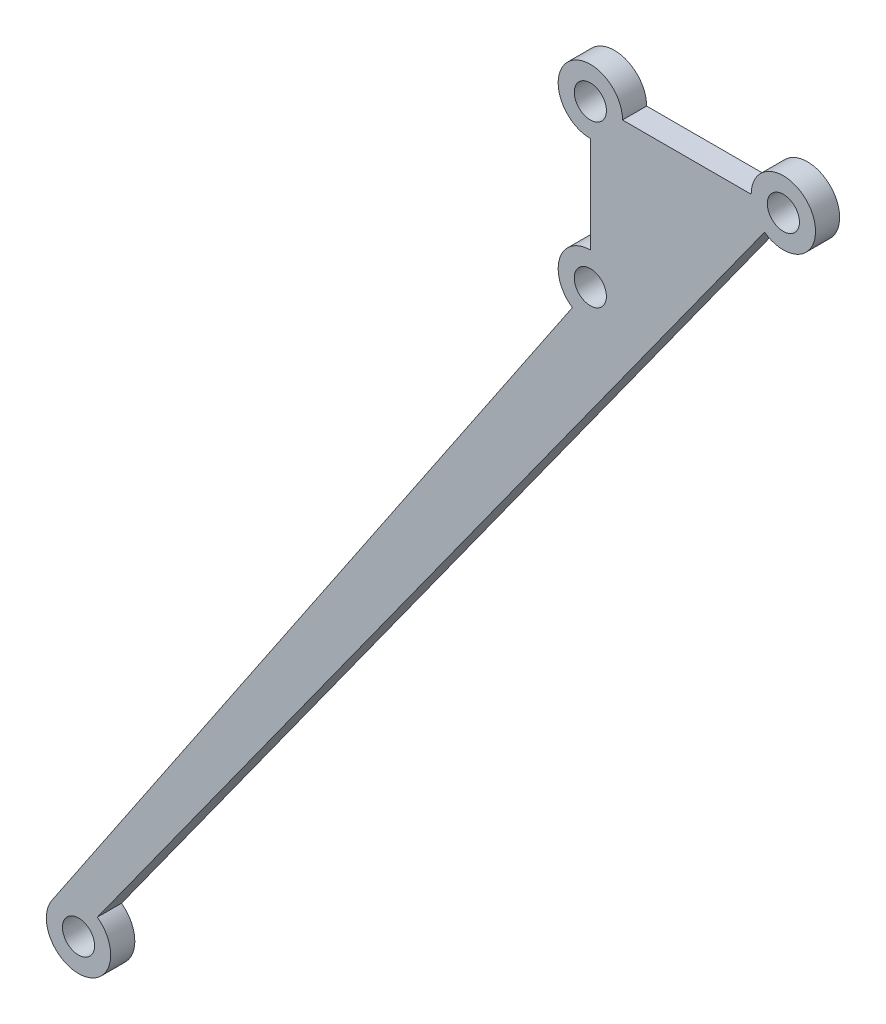
SolidWorks part; units mm, degrees
material "Zoltek Panex 33"
ref_plane "前视基准面" through (0, 0, 0) normal (0, 0, 1) x (1, 0, 0)
ref_plane "上视基准面" through (0, 0, 0) normal (0, 1, 0) x (1, 0, 0)
ref_plane "右视基准面" through (0, 0, 0) normal (1, 0, 0) x (0, 0, -1)
sketch "草图1" plane through (0, 0, 0) normal (0, 0, 1) x (1, 0, 0)
  line L4 (10.8315, -1.6232) -> (-30.6492, -59.2457)
  line L6 (-1.1165, -11.6593) -> (-33.477, -59.7523)
  line L7 (2, 0) -> (10, 0)
  line L8 (0, -2) -> (0, -8)
  arc A5 (10.8315, -1.6232) -> (10, 0) centre (12, 0) ccw
  arc A6 (2, 0) -> (0, -2) centre (0, 0) ccw
  arc A7 (0, -8) -> (-1.1165, -11.6593) centre (0, -10) ccw
  circle A8 centre (-31.8176, -60.8688) radius 1
  arc A9 (-33.477, -59.7523) -> (-30.6492, -59.2457) centre (-31.8176, -60.8688) ccw
  circle A10 centre (0, 0) radius 1
  circle A11 centre (12, 0) radius 1
  circle A12 centre (0, -10) radius 1
  dimension "D1" = 12
  dimension "D3" = 60
  dimension "D4" = 75
  dimension "D5" = 2
  dimension "D6" = 2
  dimension "D7" = 4
  dimension "D8" = 4
  dimension "D9" = 4
  dimension "D10" = 2
  dimension "D11" = 2
  dimension "D12" = 4
  dimension "D2" = 10
extrude "凸台-拉伸1" add sketch "草图1" along normal blind 1.5
